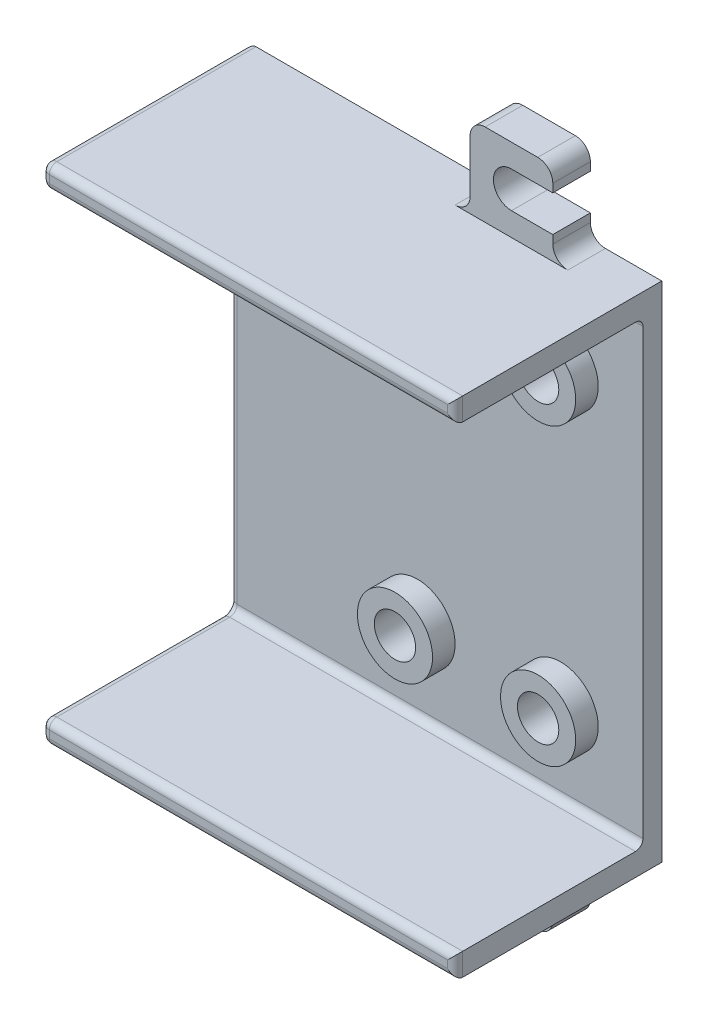
SolidWorks part; units mm, degrees
material "ABS"
ref_plane "X-Y Datum" through (0, 0, 0) normal (0, 0, 1) x (1, 0, 0)
ref_plane "X-Z Datum" through (0, 0, 0) normal (0, 1, 0) x (1, 0, 0)
ref_plane "Y-Z Datum" through (0, 0, 0) normal (1, 0, 0) x (0, 0, -1)
sketch "Sketch1" plane through (0, 0, 0) normal (0, 0, 1) x (1, 0, 0)
  line L1 (-27.5, 33.5) -> (27.5, 33.5)
  line L2 (-27.5, 33.5) -> (-27.5, -33.5)
  line L3 (-27.5, -33.5) -> (27.5, -33.5)
  line L4 (27.5, 33.5) -> (27.5, -33.5)
  line L5 (-27.5, 33.5) -> (27.5, -33.5) construction
  line L6 (-27.5, -33.5) -> (27.5, 33.5) construction
  point P0 (0, 0)
  dimension "D1" = 55
  dimension "D2" = 67
extrude "Boss-Extrude1" add sketch "Sketch1" along normal blind 2.5
sketch "Sketch2" plane through (0, 0, 2.5) normal (0, 0, 1) x (1, 0, 0)
  line L0 (27.5, -33.5) -> (27.5, 33.5) construction
  line L1 (-27.5, 33.5) -> (27.5, 33.5)
  line L2 (-27.5, 33.5) -> (-27.5, 30.5)
  line L3 (-27.5, 30.5) -> (27.5, 30.5)
  line L4 (27.5, 33.5) -> (27.5, 30.5)
  line L5 (-27.5, 33.5) -> (-27.5, -33.5) construction
  line L6 (27.5, -33.5) -> (-27.5, -33.5)
  line L7 (27.5, -33.5) -> (27.5, -30.5)
  line L8 (27.5, -30.5) -> (-27.5, -30.5)
  line L9 (-27.5, -33.5) -> (-27.5, -30.5)
  dimension "D1" = 3
extrude "Boss-Extrude2" add sketch "Sketch2" along normal blind 25
sketch "Sketch3" plane through (0, 0, 2.5) normal (0, 0, 1) x (1, 0, 0)
  circle A0 centre (-2.504, 19.6215) radius 2.75
  circle A1 centre (16.546, 19.6215) radius 2.75
  circle A2 centre (16.546, -19.6215) radius 2.75
  circle A3 centre (-2.504, -19.6215) radius 2.75
  circle A4 centre (-2.504, 19.6215) radius 5
  circle A5 centre (16.546, 19.6215) radius 5
  circle A6 centre (16.546, -19.6215) radius 5
  circle A7 centre (-2.504, -19.6215) radius 5
  dimension "D1" = 5.5
  dimension "D2" = 10
extrude "Boss-Extrude3" add sketch "Sketch3" along normal blind 3
sketch "Sketch4" plane through (0, 0, 2.5) normal (0, 0, 1) x (1, 0, 0)
  circle A0 centre (16.546, -19.6215) radius 2.75 construction
  circle A1 centre (-2.504, -19.6215) radius 2.75 construction
  circle A2 centre (16.546, 19.6215) radius 2.75 construction
  circle A3 centre (-2.504, 19.6215) radius 2.75 construction
  circle A4 centre (16.546, -19.6215) radius 2.75
  circle A5 centre (-2.504, -19.6215) radius 2.75
  circle A6 centre (16.546, 19.6215) radius 2.75
  circle A7 centre (-2.504, 19.6215) radius 2.75
extrude "Cut-Extrude1" cut sketch "Sketch4" against normal blind 2
sketch "Sketch5" plane through (0, 0, 0) normal (0, 0, -1) x (-1, 0, 0)
  line L0 (-27.5, 33.5) -> (27.5, 33.5) construction
  line L1 (-18, 33.5) -> (-7, 33.5)
  line L2 (-18, 33.5) -> (-18, 44.5)
  line L3 (-18, 44.5) -> (-7, 44.5)
  line L4 (-7, 33.5) -> (-7, 44.5)
  line L5 (-12.5, 44.5) -> (-12.5, 33.5)
  line L6 (-27.5, -33.5) -> (-27.5, 33.5) construction
  circle A0 centre (-12.5, 39) radius 2 construction
  line M9 (27.5, 33.5) -> (-27.5, 33.5)
  dimension "D3" = 4
  dimension "D1" = 11
  dimension "D2" = 11
  dimension "D4" = 15
extrude "Boss-Extrude4" add sketch "Sketch5" against normal blind 5 contours L3 L5 L4 M9 | L5 L3 L2 L1
hole_wizard "M4 Clearance Hole1" positions "Sketch8" profile "Sketch7" hole size "M4" standard "ANSI Metric" end condition through all
sketch "Sketch8" plane through (0, 0, 5) normal (0, 0, 1) x (1, 0, 0)
  point P0 (12.5, 39)
sketch "Sketch7" plane through (12.5, 39, 5) normal (1, 0, 0) x (0, -1, 0)
  line L0 (0, 0) -> (0, 5)
  line L1 (0, 5) -> (2.4, 5)
  line L2 (2.4, 5) -> (2.4, 0)
  line L5 (2.4, 0) -> (0, 0)
  line L11 (0, -6.35) -> (0, 107.95) construction
  dimension "Thru Hole Dia." = 4.8
  dimension "Thru Hole Depth" = 5
sketch "Sketch9" plane through (0, 0, 5) normal (0, 0, 1) x (1, 0, 0)
  line L0 (12.5, 41.4) -> (18, 41.4)
  line L1 (12.5, 44.5) -> (12.5, 33.5) construction
  line L2 (18, 33.5) -> (18, 44.5) construction
  line L3 (12.5, 36.6) -> (18, 36.6)
  line L8 (18, 44.5) -> (7, 44.5)
  line L9 (7, 44.5) -> (7, 33.5)
  line L10 (7, 33.5) -> (18, 33.5)
  line L11 (18, 33.5) -> (18, 44.5)
  line L12 (18, 44.5) -> (7, 44.5)
  line L13 (7, 44.5) -> (7, 33.5)
  line L14 (7, 33.5) -> (18, 33.5)
  line L15 (18, 33.5) -> (18, 44.5)
  circle A0 centre (12.5, 39) radius 2.4 construction
  circle A1 centre (12.5, 39) radius 2.4
  circle M5 centre (12.5, 39) radius 2.4
  line M9 (18, 33.5) -> (18, 44.5)
  dimension "D1" = 0
extrude "Cut-Extrude2" [suppressed] cut sketch "Sketch9" against normal through all contours L3 L0 M5 M9
mirror "Mirror2" about plane through (0, 0, 0) normal (0, 1, 0) of "Cut-Extrude2", "M4 Clearance Hole1", "Boss-Extrude4"
fillet "Fillet2" [suppressed] radius 2
fillet "Fillet3" radius 2 8 edges at (18, -33.5, 2.5) (18, -44.5, 2.5) (7, -44.5, 2.5) (7, -33.5, 2.5) (18, 33.5, 2.5) (18, 44.5, 2.5) (7, 44.5, 2.5) (7, 33.5, 2.5)
fillet "Fillet4" radius 1 16 edges at (0, 33.5, 27.5) (27.5, 32, 27.5) (0, 30.5, 27.5) (-27.5, 32, 27.5) (0, -33.5, 27.5) (-27.5, -32, 27.5) (0, -30.5, 27.5) (27.5, -32, 27.5) (0, 30.5, 2.5) (0, -30.5, 2.5) (-27.5, 33.5, 13.75) (-27.5, 30.5, 15) (-27.5, 0, 2.5) (-27.5, -30.5, 15) (-27.5, -33.5, 13.75) (-27.5, 0, 0)
sketch "Sketch10" plane through (0, 0, 5) normal (0, 0, 1) x (1, 0, 0)
  line L0 (12.5, 41.4) -> (18, 41.4)
  line L1 (18, 35.5) -> (18, 42.5) construction
  line L2 (12.5, 36.6) -> (18, 36.6)
  line L3 (18, 35.5) -> (18, 42.5)
  circle A0 centre (12.5, 39) radius 2.4 construction
  circle A1 centre (12.5, 39) radius 2.4
extrude "Cut-Extrude3" cut sketch "Sketch10" against normal through all contours A1 L2 L3 L0
mirror "Mirror3" about plane through (0, 0, 0) normal (0, 1, 0) of "Cut-Extrude3"
